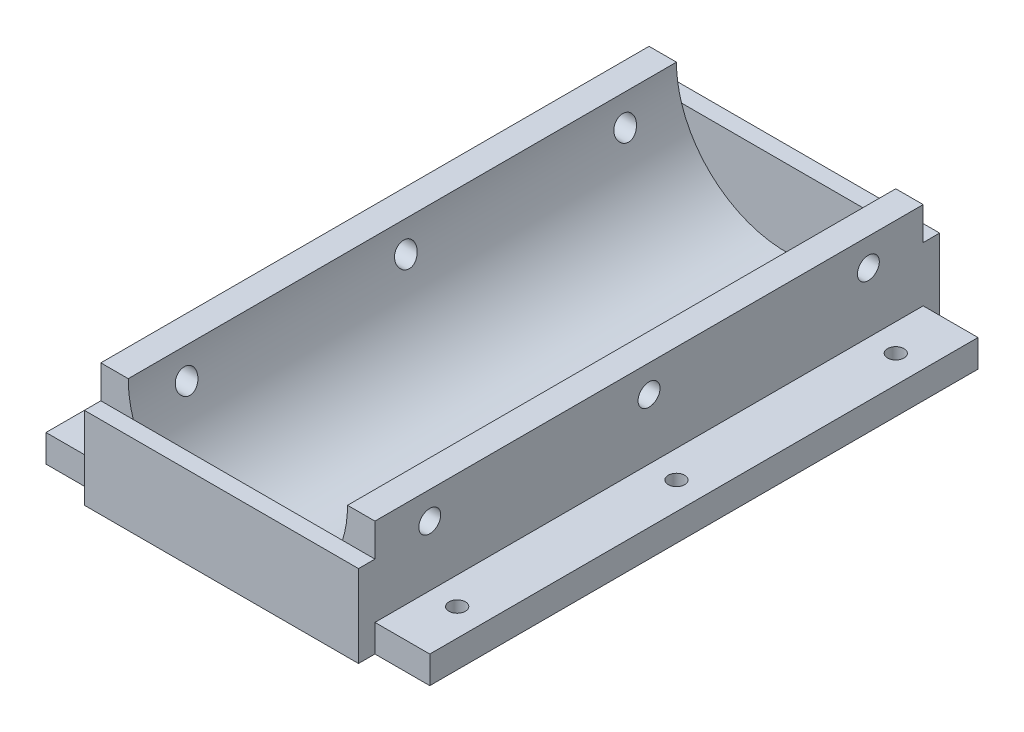
SolidWorks part; units mm, degrees
ref_plane "Front Plane" through (0, 0, 0) normal (0, 0, 1) x (1, 0, 0)
ref_plane "Top Plane" through (0, 0, 0) normal (0, 1, 0) x (1, 0, 0)
ref_plane "Right Plane" through (0, 0, 0) normal (1, 0, 0) x (0, 0, -1)
sketch "Sketch1" plane through (0, 0, 0) normal (0, 0, 1) x (1, 0, 0)
  line L0 (-25, 0) -> (25, 0) construction
  line L1 (25, -21) -> (-25, -21)
  line L2 (25, -21) -> (25, 0)
  line L4 (-25, -21) -> (-25, 0)
  line L5 (25, -21) -> (-25, 21) construction
  line L6 (25, 21) -> (-25, -21) construction
  line L7 (-25, 0) -> (-20, 0)
  line L8 (20, 0) -> (25, 0)
  line L10 (25, -16) -> (35, -16)
  line L11 (25, -16) -> (25, -21)
  line L12 (25, -21) -> (35, -21)
  line L13 (35, -16) -> (35, -21)
  line L14 (-25, -21) -> (-35, -21)
  line L15 (-25, -21) -> (-25, -16)
  line L16 (-25, -16) -> (-35, -16)
  line L17 (-35, -21) -> (-35, -16)
  arc A0 (-20, 0) -> (20, 0) centre (0, 0) ccw
  point P0 (0, 0)
  point P12 (0, 0)
  dimension "D1" = 40
  dimension "D2" = 21
  dimension "D3" = 50
  dimension "D4" = 10
  dimension "D5" = 5
  dimension "D6" = 10
  dimension "D7" = 5
extrude "Boss-Extrude2" add sketch "Sketch1" along normal mid plane 100 contours A0 L7 L4 L1 L2 L8 | L17 L14 L4 L16 | L11 L10 L13 L12
sketch "Sketch2" plane through (0, -16, 0) normal (0, 1, 0) x (1, 0, 0)
  line L0 (30, 50) -> (30, -50) construction
  line L1 (25, 50) -> (35, 50) construction
  line L2 (25, -50) -> (35, -50) construction
  line L4 (-25, -50) -> (-35, -50) construction
  line L5 (-30, -50) -> (-30, 50) construction
  line L6 (-25, 50) -> (-35, 50) construction
  circle A0 centre (-30, 40) radius 1.5
  circle A1 centre (-30, 0) radius 1.5
  circle A2 centre (-30, -40) radius 1.5
  circle A3 centre (30, 40) radius 1.5
  circle A4 centre (30, 0) radius 1.5
  circle A5 centre (30, -40) radius 1.5
  dimension "D1" = 3
  dimension "D2" = 40
  dimension "D3" = 40
extrude "Cut-Extrude1" cut sketch "Sketch2" against normal blind 100
sketch "Sketch5" plane through (25, 0, 0) normal (1, 0, 0) x (0, 0, -1)
  line L0 (-50, -16) -> (-50, 0) construction
  line L3 (-50, 0) -> (50, 0) construction
  circle A0 centre (-40, -5) radius 2
  circle A1 centre (0, -5) radius 2
  circle A2 centre (40, -5) radius 2
  dimension "D1" = 50
  dimension "D2" = 4
  dimension "D3" = 40
  dimension "D5" = 5
  dimension "D4" = 40
extrude "Cut-Extrude3" cut sketch "Sketch5" against normal blind 100
sketch "Sketch6" plane through (0, 0, 50) normal (0, 0, 1) x (1, 0, 0)
  line L0 (-25, -16) -> (-25, 0) construction
  line L1 (-25, -6) -> (25, -6)
  line L2 (-25, -6) -> (-25, -21)
  line L3 (-25, -21) -> (25, -21)
  line L4 (25, -6) -> (25, -21)
  line L5 (35, -21) -> (-35, -21) construction
  line L6 (25, -16) -> (25, 0) construction
  dimension "D1" = 15
extrude "Boss-Extrude3" add sketch "Sketch6" along normal blind 3
mirror "Mirror2" about plane through (0, 0, 0) normal (0, 0, 1) of "Boss-Extrude3"
